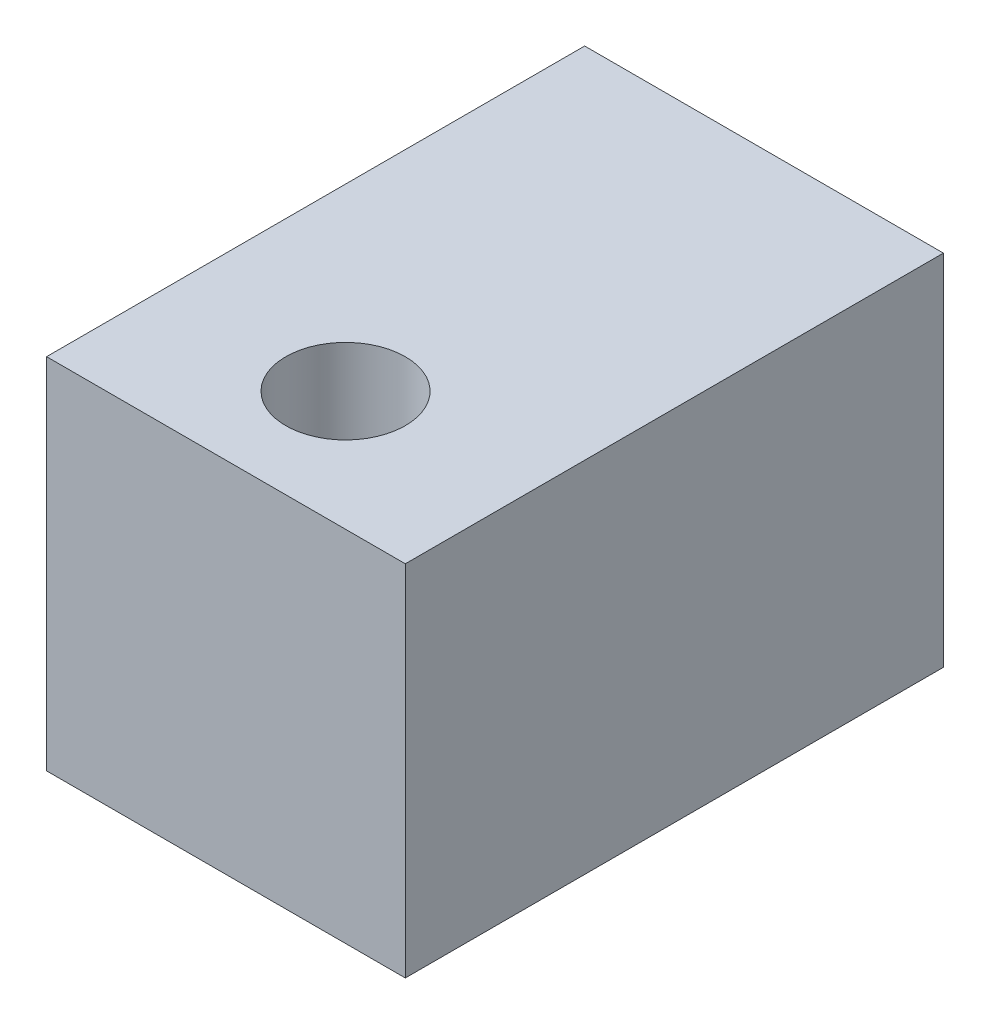
SolidWorks part; units mm, degrees
ref_plane "前视基准面" through (0, 0, 0) normal (0, 0, 1) x (1, 0, 0)
ref_plane "上视基准面" through (0, 0, 0) normal (0, 1, 0) x (1, 0, 0)
ref_plane "右视基准面" through (0, 0, 0) normal (1, 0, 0) x (0, 0, -1)
sketch "草图1" plane through (0, 0, 0) normal (0, 0, 1) x (1, 0, 0)
  line L1 (0, 0) -> (12, 0)
  line L2 (0, 0) -> (0, 12)
  line L3 (0, 12) -> (12, 12)
  line L4 (12, 0) -> (12, 12)
  line L5 (1, 1) -> (11, 1)
  line L6 (1, 1) -> (1, 11)
  line L7 (1, 11) -> (11, 11)
  line L8 (11, 1) -> (11, 11)
  point P5 (1, 1)
extrude "凸台-拉伸1" add sketch "草图1" along normal blind 10
sketch "草图2" plane through (0, 0, 10) normal (0, 0, 1) x (1, 0, 0)
  line L1 (0, 12) -> (12, 12)
  line L2 (0, 12) -> (0, 0)
  line L3 (0, 0) -> (12, 0)
  line L4 (12, 12) -> (12, 0)
extrude "凸台-拉伸2" add sketch "草图2" along normal blind 8
sketch "草图3" plane through (0, 0, 0) normal (0, -1, 0) x (-1, 0, 0)
  circle A0 centre (-6, -14) radius 2
  point P0 (-6, -14)
  point P3 (0, 0)
extrude "切除-拉伸3" cut sketch "草图3" against normal blind 12
